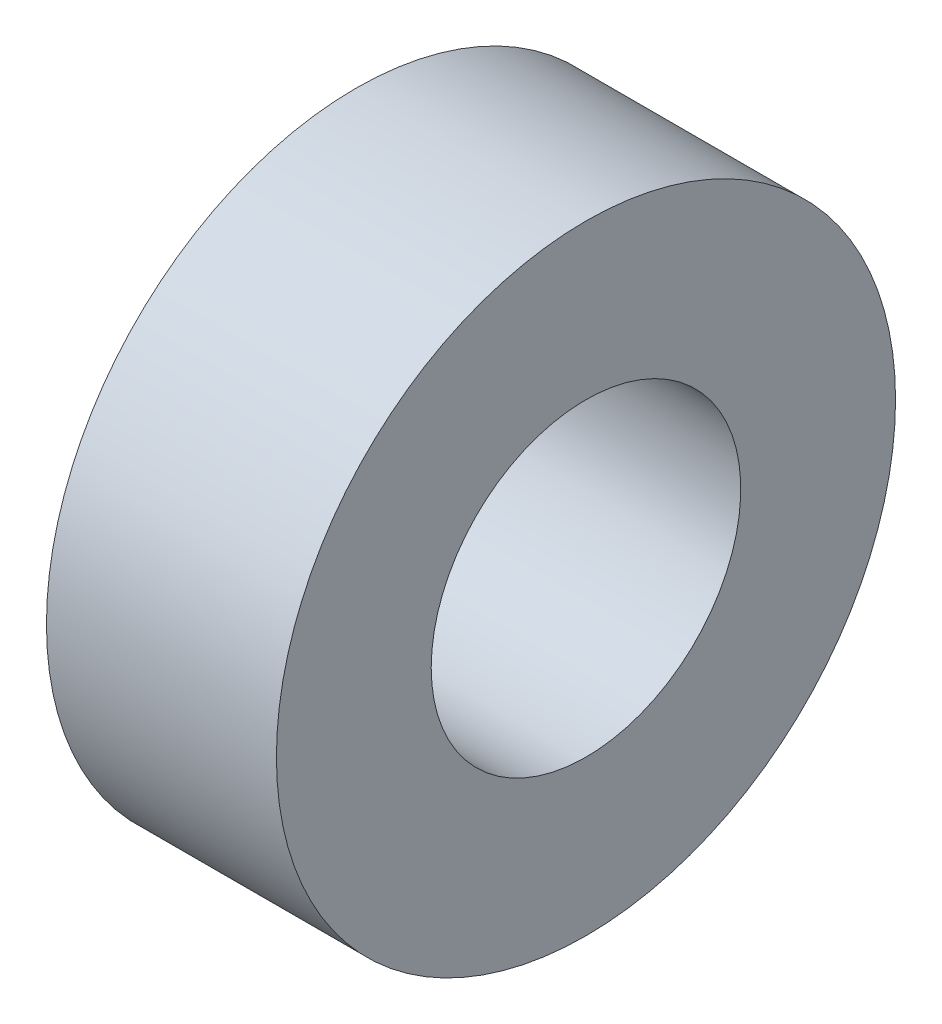
SolidWorks part; units mm, degrees
material "ABS"
ref_plane "정면" through (0, 0, 0) normal (0, 0, 1) x (1, 0, 0)
ref_plane "윗면" through (0, 0, 0) normal (0, 1, 0) x (1, 0, 0)
ref_plane "우측면" through (0, 0, 0) normal (1, 0, 0) x (0, 0, -1)
sketch "Sketch15" plane through (0, 0, 0) normal (0, 0, 1) x (1, 0, 0)
  line L1 (851, 1496) -> (877, 1496)
  line L2 (851, 1496) -> (851, 1461)
  line L3 (851, 1461) -> (877, 1461)
  line L4 (877, 1496) -> (877, 1461)
  dimension "D1" = 1461
  dimension "D2" = 851
  dimension "D3" = 35
  dimension "D4" = 26
revolve "Revolve1" add sketch "Sketch15" angle 360 about L3
sketch "Sketch16" plane through (0, 0, 0) normal (0, 0, 1) x (1, 0, 0)
  line L0 (851, 1496) -> (851, 1461) construction
  line L1 (877, 1461) -> (851, 1461)
  line L2 (877, 1461) -> (877, 1478.5)
  line L3 (877, 1478.5) -> (851, 1478.5)
  line L4 (851, 1461) -> (851, 1478.5)
  dimension "D1" = 17.5
revolve "Cut-Revolve1" cut sketch "Sketch16" angle 360 about L3
scale "Scale1" bodies to scale 127 scale about origin uniform scaling yes scale factor 0.1
equation "\"Mass\"= \"SW-질량\" / 1000"
